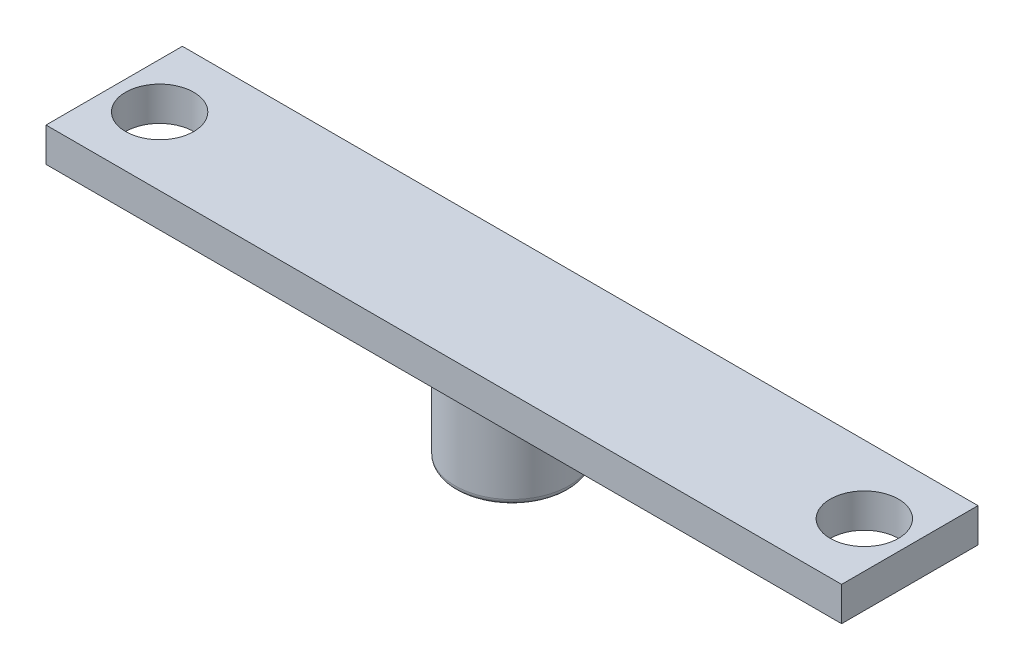
SolidWorks part; units mm, degrees
ref_plane "Front Plane" through (0, 0, 0) normal (0, 0, 1) x (1, 0, 0)
ref_plane "Top Plane" through (0, 0, 0) normal (0, 1, 0) x (1, 0, 0)
ref_plane "Right Plane" through (0, 0, 0) normal (1, 0, 0) x (0, 0, -1)
sketch "Sketch1" plane through (0, 0, 0) normal (0, 1, 0) x (1, 0, 0)
  line L1 (-35, -6) -> (35, -6)
  line L2 (-35, -6) -> (-35, 6)
  line L3 (-35, 6) -> (35, 6)
  line L4 (35, -6) -> (35, 6)
  line L5 (-35, -6) -> (35, 6) construction
  line L6 (-35, 6) -> (35, -6) construction
  point P0 (0, 0)
  dimension "D1" = 12
extrude "Boss-Extrude1" add sketch "Sketch1" along normal blind 3
sketch "Sketch3" plane through (0, 3, 0) normal (0, 1, 0) x (1, 0, 0)
  line L0 (-31, 0) -> (31, 0) construction
  circle A0 centre (-31, 0) radius 3
  circle A1 centre (31, 0) radius 3
  point P2 (0, 0)
  point P5 (0, 0)
  dimension "D1" = 3
  dimension "D2" = 62
extrude "Cut-Extrude1" cut sketch "Sketch3" against normal through all contours A1 | A0
sketch "Sketch4" plane through (0, 0, 0) normal (0, -1, 0) x (1, 0, 0)
  circle A0 centre (0, 0) radius 5
  dimension "D1" = 5
extrude "Boss-Extrude2" add sketch "Sketch4" along normal blind 8
fillet "Fillet2" radius 0.5 2 edges at (0, 0, -5) (0, -8, -5)
